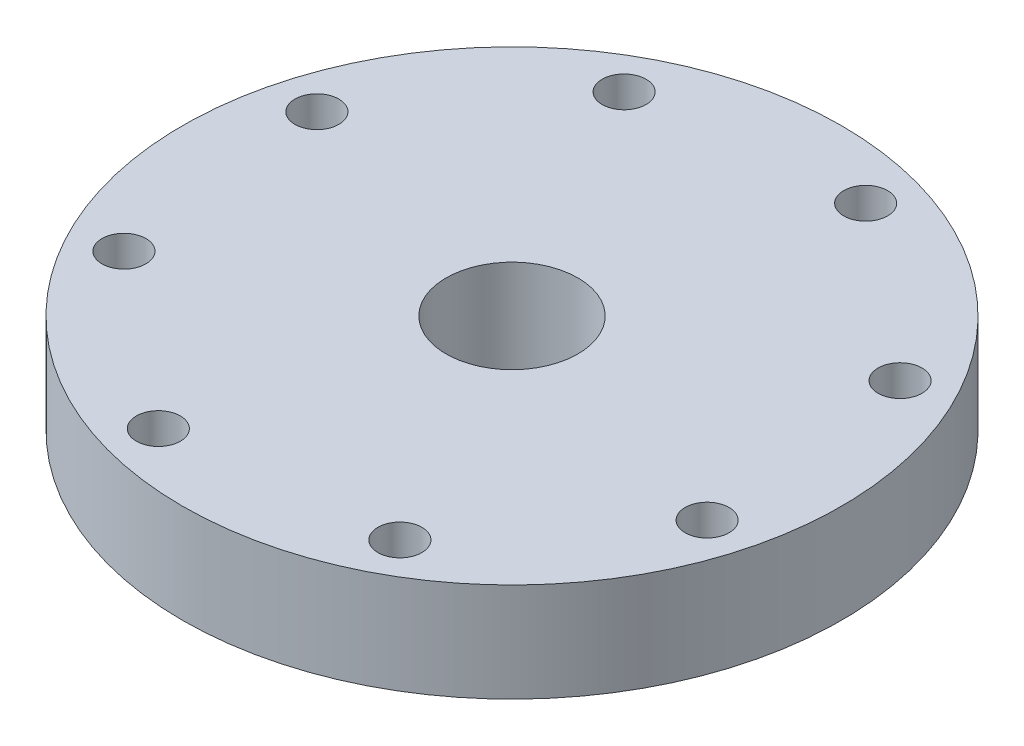
SolidWorks part; units mm, degrees
ref_plane "正面" through (0, 0, 0) normal (0, 0, 1) x (1, 0, 0)
ref_plane "平面" through (0, 0, 0) normal (0, 1, 0) x (1, 0, 0)
ref_plane "右側面" through (0, 0, 0) normal (1, 0, 0) x (0, 0, -1)
sketch "ｽｹｯﾁ1" plane through (0, 0, 0) normal (0, 1, 0) x (1, 0, 0)
  circle A0 centre (0, 0) radius 15
  dimension "D1" = 30
extrude "ﾎﾞｽ - 押し出し1" add sketch "ｽｹｯﾁ1" along normal mid plane 4.5
sketch "ｽｹｯﾁ3" plane through (0, 2.25, 0) normal (0, 1, 0) x (1, 0, 0)
  circle A0 centre (-11.3826, -6.2799) radius 1
  circle A1 centre (0, 0) radius 15 construction
  circle A2 centre (-12.4893, 3.6081) radius 1
  circle A3 centre (-6.2799, 11.3826) radius 1
  circle A4 centre (3.6081, 12.4893) radius 1
  circle A5 centre (11.3826, 6.2799) radius 1
  circle A6 centre (12.4893, -3.6081) radius 1
  circle A7 centre (6.2799, -11.3826) radius 1
  circle A8 centre (-3.6081, -12.4893) radius 1
  dimension "D1" = 2
  dimension "D2" = 13
  dimension "D3" = 8
extrude "ｶｯﾄ - 押し出し1" cut sketch "ｽｹｯﾁ3" against normal blind 5
sketch "ｽｹｯﾁ4" plane through (0, -2.25, 0) normal (0, -1, 0) x (1, 0, 0)
  circle A0 centre (0, 0) radius 3
  dimension "D1" = 6
extrude "ｶｯﾄ - 押し出し2" cut sketch "ｽｹｯﾁ4" against normal blind 4.5
